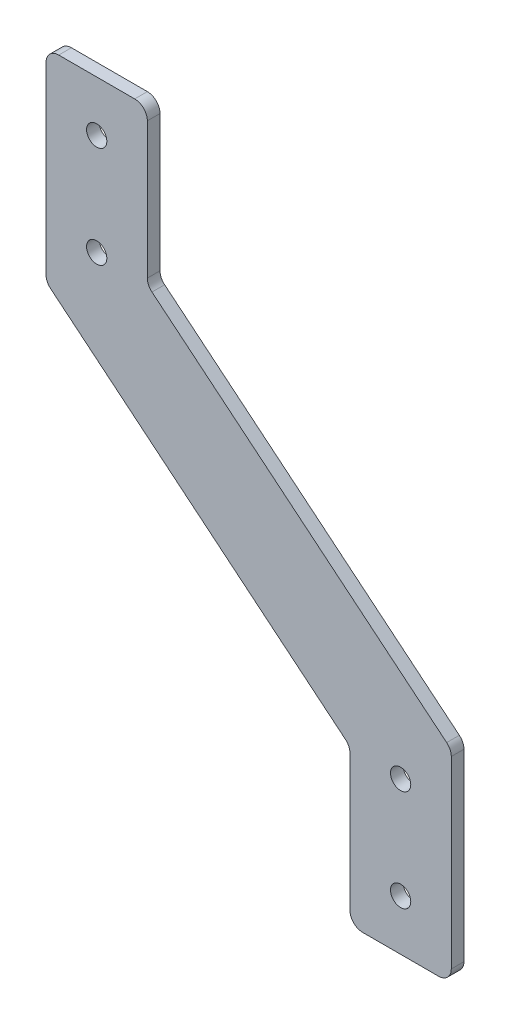
SolidWorks part; units mm, degrees
material "6061-T6 (SS)"
ref_plane "Front Plane" through (0, 0, 0) normal (0, 0, 1) x (1, 0, 0)
ref_plane "Top Plane" through (0, 0, 0) normal (0, 1, 0) x (1, 0, 0)
ref_plane "Right Plane" through (0, 0, 0) normal (1, 0, 0) x (0, 0, -1)
sketch "Sketch1" plane through (0, 0, 0) normal (0, 0, 1) x (1, 0, 0)
  line L0 (0, 0) -> (0, 25.4) construction
  line L1 (0, -55) -> (0, 55) construction
  line L2 (-76.2, 101.6) -> (-76.2, 127) construction
  line L3 (-12.7, -12.7) -> (12.7, -12.7)
  line L4 (12.7, -12.7) -> (12.7, 38.1)
  line L5 (12.7, 38.1) -> (-63.5, 100.8832)
  line L6 (-63.5, 100.8832) -> (-63.5, 139.7)
  line L7 (-63.5, 139.7) -> (-88.9, 139.7)
  line L8 (-88.9, 139.7) -> (-88.9, 88.9)
  line L9 (-88.9, 88.9) -> (-12.7, 26.1168)
  line L10 (-12.7, 26.1168) -> (-12.7, -12.7)
  circle A0 centre (0, 25.4) radius 2.54
  circle A1 centre (0, 0) radius 2.54
  circle A2 centre (-76.2, 127) radius 2.54
  circle A3 centre (-76.2, 101.6) radius 2.54
  point P20 (0, -12.7)
  point P25 (-76.2, 139.7)
  dimension "D2" = 5.08
  dimension "D1" = 25.4
  dimension "D3" = 25.4
  dimension "D4" = 76.2
  dimension "D5" = 25.4
  dimension "D6" = 25.4
  dimension "D7" = 12.7
  dimension "D8" = 12.7
  dimension "D9" = 12.7
  dimension "D10" = 25.4
  dimension "D11" = 12.7
  dimension "D12" = 76.2
extrude "Boss-Extrude1" add sketch "Sketch1" along normal blind 3.175
fillet "Fillet1" radius 3.175 8 edges at (-88.9, 88.9, 1.5875) (-88.9, 139.7, 1.5875) (-63.5, 139.7, 1.5875) (12.7, 38.1, 1.5875) (12.7, -12.7, 1.5875) (-12.7, -12.7, 1.5875) (-12.7, 26.1168, 1.5875) (-63.5, 100.8832, 1.5875)
